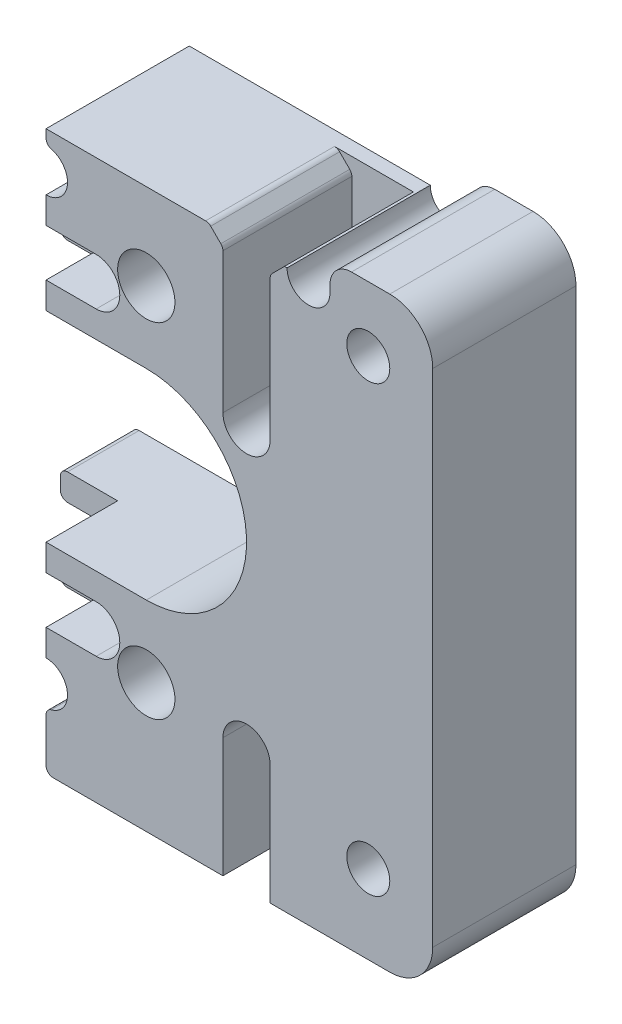
SolidWorks part; units mm, degrees
ref_plane "Front Plane" through (0, 0, 0) normal (0, 0, 1) x (1, 0, 0)
ref_plane "Top Plane" through (0, 0, 0) normal (0, 1, 0) x (1, 0, 0)
ref_plane "Right Plane" through (0, 0, 0) normal (1, 0, 0) x (0, 0, -1)
sketch "Sketch14" plane through (0, 0, 0) normal (0, 0, 1) x (1, 0, 0)
  line L0 (27, -8.5) -> (27, 0)
  line L1 (0, -14) -> (7, -14)
  line L2 (0, -14) -> (0, 0)
  line L3 (0, 0) -> (27, 0)
  line L4 (27, -42) -> (27, -33.5)
  line L5 (27, -8.5) -> (27, -33.5)
  line L6 (0, -28) -> (0, -42)
  line L7 (27, -42) -> (0, -42)
  line L9 (7, -28) -> (0, -28)
  arc A0 (7, -28) -> (7, -14) centre (7, -21) ccw
  dimension "D5" = 27
  dimension "D1" = 7
  dimension "D2" = 21
  dimension "D4" = 42
  dimension "D6" = 7
  dimension "D8" = 25
extrude "Boss-Extrude5" add sketch "Sketch14" along normal blind 10
sketch "Sketch32" plane through (0, 0, 0) normal (-1, 0, 0) x (0, 0, 1)
  line L0 (0, 0) -> (0, -14) construction
  line L1 (0, -7) -> (5, -7)
  line L2 (0, -7) -> (0, -14)
  line L3 (0, -14) -> (5, -14)
  line L4 (5, -7) -> (5, -14)
  line L5 (10, -14) -> (0, -14) construction
  line L6 (10, -28) -> (0, -28) construction
  line L7 (5, -28) -> (0, -28)
  line L8 (5, -28) -> (5, -35)
  line L9 (5, -35) -> (0, -35)
  line L10 (0, -28) -> (0, -35)
  line L11 (0, -28) -> (0, -42) construction
  dimension "D1" = 7
  dimension "D2" = 5
  dimension "D3" = 7
extrude "Boss-Extrude6" add sketch "Sketch32" along normal blind 4
sketch "Sketch15" plane through (0, 0, 10) normal (0, 0, 1) x (1, 0, 0)
  line L4 (27, 0) -> (0, 0) construction
  circle A0 centre (7, -9) radius 2
  circle A1 centre (22.5, -5.5) radius 1.5
  circle A2 centre (-8.5, -9) radius 1.5 construction
  circle A3 centre (22.5, -36.5) radius 1.5
  circle A4 centre (7, -33) radius 2
  circle A5 centre (-8.5, -36.5) radius 1.5
  point P15 (7, -21)
  dimension "D1" = 3
  dimension "D2" = 4
  dimension "D3" = 15.5
  dimension "D4" = 12
  dimension "D5" = 7
  dimension "D6" = 5.5
  dimension "D7" = 31
  dimension "D8" = 31
  dimension "D9" = 12
  dimension "D11" = 31
extrude "Cut-Extrude8" cut sketch "Sketch15" against normal through all
sketch "Sketch33" plane through (0, 0, 10) normal (0, 0, 1) x (1, 0, 0)
  line L3 (-4, -31.5) -> (3.5, -31.5) construction
  line L4 (-4, -29.85) -> (3.5, -29.85)
  line L8 (-4, -33.15) -> (3.5, -33.15)
  line L9 (3, -21) -> (-4.5, -21) construction
  line L10 (-4, -10.5) -> (3.5, -10.5) construction
  line L11 (-4, -12.15) -> (3.5, -12.15)
  line L12 (-4, -8.85) -> (3.5, -8.85)
  line L13 (-4, -35) -> (-4, -28) construction
  line L14 (-4, -14) -> (0, -14) construction
  line L15 (-4, -28) -> (0, -28) construction
  arc A0 (-4, -29.85) -> (-4, -33.15) centre (-4, -31.5) ccw
  arc A1 (3.5, -33.15) -> (3.5, -29.85) centre (3.5, -31.5) ccw
  arc A3 (-4, -12.15) -> (-4, -8.85) centre (-4, -10.5) cw
  arc A6 (3.5, -8.85) -> (3.5, -12.15) centre (3.5, -10.5) cw
  point P4 (-0.25, -31.5)
  point P19 (-0.25, -10.5)
  dimension "D1" = 7.5
extrude "Cut-Extrude18" cut sketch "Sketch33" against normal blind 9
sketch "Sketch34" plane through (0, 0, 10) normal (0, 0, 1) x (1, 0, 0)
  line L0 (0, -5.5) -> (-4.5, -5.5) construction
  line L1 (0, 0) -> (0, -8.85) construction
  line L2 (0, -7) -> (-4.5, -7)
  line L3 (0, -4) -> (-4.5, -4)
  line L4 (-4, -7) -> (0, -7) construction
  line L5 (0, -36.5) -> (-4, -36.5) construction
  line L6 (0, -33.15) -> (0, -42) construction
  line L7 (0, -38) -> (-4, -38)
  line L8 (0, -35) -> (-4, -35)
  line L9 (-4, -35) -> (0, -35) construction
  line L12 (-4, -35) -> (-4, -33.15) construction
  arc A0 (0, -7) -> (0, -4) centre (0, -5.5) ccw
  arc A1 (-4.5, -4) -> (-4.5, -7) centre (-4.5, -5.5) ccw
  arc A2 (0, -38) -> (0, -35) centre (0, -36.5) ccw
  arc A3 (-4, -35) -> (-4, -38) centre (-4, -36.5) ccw
  point P4 (-2.25, -5.5)
  point P15 (-2, -36.5)
  dimension "D1" = 1.5
extrude "Cut-Extrude19" cut sketch "Sketch34" against normal through all
sketch "Sketch20" plane through (0, 0, 10) normal (0, 0, 1) x (1, 0, 0)
  line L0 (27, 0) -> (0, 0) construction
  line L1 (16, 7.221) -> (-2.5732, 7.221)
  line L2 (16, 7.221) -> (16, -2.67)
  line L3 (16, -2.67) -> (-2.5732, -2.67)
  line L4 (-2.5732, 7.221) -> (-2.5732, -2.67)
  line L5 (0, 0) -> (0, -4) construction
  dimension "D1" = 2.67
  dimension "D2" = 16
extrude "Cut-Extrude12" cut sketch "Sketch20" against normal through all
sketch "Sketch28" plane through (0, 0, 10) normal (0, 0, 1) x (1, 0, 0)
  line L0 (16, -2.67) -> (16, 0) construction
  line L1 (27, 0) -> (16, 0)
  line L2 (27, 0) -> (27, -1)
  line L3 (27, -1) -> (16, -1)
  line L4 (16, 0) -> (16, -1)
  dimension "D1" = 1
extrude "Cut-Extrude15" cut sketch "Sketch28" against normal blind 10
sketch "Sketch37" plane through (0, -42, 0) normal (0, -1, 0) x (1, 0, 0)
  line L0 (0, 0) -> (27, 0) construction
  line L1 (10.5, 5) -> (17.5, 5)
  line L2 (10.5, 5) -> (10.5, 0)
  line L3 (10.5, 0) -> (17.5, 0)
  line L4 (17.5, 5) -> (17.5, 0)
  line L5 (14, 5) -> (14, 2.4685) construction
  line L6 (7, 10) -> (7, 0) construction
  dimension "D1" = 7
  dimension "D2" = 7
  dimension "D3" = 5
extrude "Boss-Extrude7" add sketch "Sketch37" along normal blind 1
sketch "Sketch19" plane through (0, 0, 10) normal (0, 0, 1) x (1, 0, 0)
  line L0 (17.5, -43) -> (10.5, -43) construction
  line L6 (14, -33.65) -> (14, -43) construction
  line L7 (15.65, -33.65) -> (15.65, -43)
  line L8 (12.35, -33.65) -> (12.35, -43)
  line L14 (0, -42) -> (27, -42) construction
  arc A1 (7, -28) -> (7, -14) centre (7, -21) ccw construction
  arc A5 (15.65, -33.65) -> (12.35, -33.65) centre (14, -33.65) ccw
  arc A8 (12.35, -43) -> (15.65, -43) centre (14, -43) ccw
  point P17 (14, -38.325)
  dimension "D5" = 8.35
  dimension "D2" = 1.65
  dimension "D1" = 7
extrude "Cut-Extrude11" cut sketch "Sketch19" against normal blind 9
sketch "Sketch35" plane through (0, 0, 10) normal (0, 0, 1) x (1, 0, 0)
  line L0 (27, -42) -> (27, -1) construction
  line L1 (14, -14) -> (14, 1.1203) construction
  line L2 (11.35, -3) -> (12.35, -4)
  line L3 (12.35, -4) -> (12.35, -14)
  line L4 (15.65, -14) -> (15.65, -4)
  line L5 (15.65, -4) -> (16.65, -3)
  line L6 (11.35, -3) -> (0, -3)
  line L7 (0, -2.67) -> (0, -4) construction
  line L8 (0, -3) -> (0, -2.67)
  line L9 (0, -2.67) -> (16, -2.67)
  line L10 (16, -2.67) -> (16, -1) construction
  line L11 (0, -2.67) -> (16, -2.67) construction
  line L12 (16, -2.67) -> (16, -1)
  line L13 (16, -1) -> (21.3284, -1)
  line L14 (19.8284, -2.5) -> (19.8284, -3)
  line L15 (16.65, -3) -> (16.8284, -3)
  arc A0 (12.35, -14) -> (15.65, -14) centre (14, -14) ccw
  arc A1 (16.8284, -3) -> (19.8284, -3) centre (18.3284, -3) ccw
  arc A2 (21.3284, -1) -> (19.8284, -2.5) centre (21.3284, -2.5) ccw
  dimension "D1" = 1.5
  dimension "D3" = 0.33
  dimension "D4" = 11
  dimension "D5" = 14
  dimension "D6" = 1.65
  dimension "D9" = 3
  dimension "D2" = 5.6716
  dimension "D7" = 1
  dimension "D8" = 1
extrude "Cut-Extrude20" cut sketch "Sketch35" against normal through all
sketch "Sketch39" plane through (0, 0, 0) normal (0, 0, -1) x (-1, 0, 0)
  line L0 (-15.65, -4) -> (-16.65, -3) construction
  line L1 (-15.65, -14) -> (-15.65, -4) construction
  line L2 (-12.35, -4) -> (-12.35, -14) construction
  line L3 (-11.35, -3) -> (-12.35, -4) construction
  line L4 (-15.65, -4) -> (-16.65, -3)
  line L5 (-15.65, -14) -> (-15.65, -4)
  line L6 (-12.35, -4) -> (-12.35, -14)
  line L7 (-11.35, -3) -> (-12.35, -4)
  line L8 (-16.65, -3) -> (-11.35, -3)
  arc A0 (-15.65, -14) -> (-12.35, -14) centre (-14, -14) ccw construction
  arc A1 (-15.65, -14) -> (-12.35, -14) centre (-14, -14) ccw
extrude "Boss-Extrude8" add sketch "Sketch39" against normal up to surface (1 mm away) up to face at (14, -37.9125, 1)
fillet "Fillet15" radius 3 2 edges at (27, -42, 5) (27, -1, 5)
fillet "Fillet16" radius 0.5 18 edges at (0, -42, 5) (-4, -35, 2.5) (-4, -33.15, 3) (-4, -29.85, 3) (-4, -28, 2.5) (-4, -14, 2.5) (-4, -7, 2.5) (-4, -12.15, 3) (-4, -8.85, 3) (0, -4, 5) (0, -38, 5) (10.5, -43, 2.5) (17.5, -43, 2.5) (15.65, -43, 3) (12.35, -43, 3) (15.65, -4, 5.5) (12.35, -4, 5.5) (11.35, -3, 5.5)
